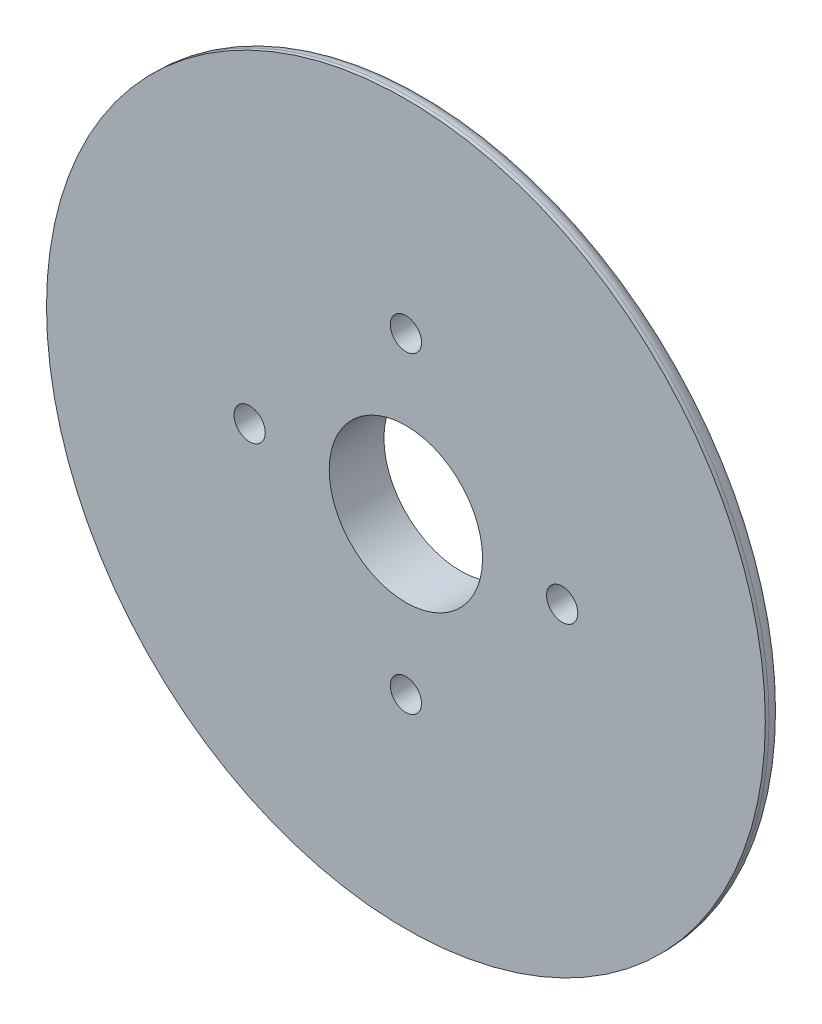
SolidWorks part; units mm, degrees
ref_plane "Front Plane" through (0, 0, 0) normal (0, 0, 1) x (1, 0, 0)
ref_plane "Top Plane" through (0, 0, 0) normal (0, 1, 0) x (1, 0, 0)
ref_plane "Right Plane" through (0, 0, 0) normal (1, 0, 0) x (0, 0, -1)
sketch "Sketch1" plane through (0, 0, 0) normal (0, 1, 0) x (1, 0, 0)
  line L0 (28, 45.5) -> (0, 45.5)
  line L1 (0, 45.5) -> (0, 16.5)
  line L2 (0, 16.5) -> (36, 16.5)
  line L3 (36, 16.5) -> (46, 26.5)
  line L4 (46, 26.5) -> (46, 40.5)
  line L5 (46, 40.5) -> (28, 45.5)
  line L6 (0, 45.5) -> (0, 16.5) construction
revolve "Revolve1" add sketch "Sketch1" angle 360 about L6
sketch "Sketch2" plane through (0, 0, -45.5) normal (0, 0, -1) x (-1, 0, 0)
  line L0 (-9.815, 0) -> (-4.9075, 8.5)
  line L1 (-4.9075, 8.5) -> (4.9075, 8.5)
  line L2 (4.9075, 8.5) -> (9.815, 0)
  line L3 (9.815, 0) -> (4.9075, -8.5)
  line L4 (4.9075, -8.5) -> (-4.9075, -8.5)
  line L5 (-4.9075, -8.5) -> (-9.815, 0)
extrude "Boss-Extrude1" add sketch "Sketch2" along normal blind 4
sketch "Sketch3" plane through (0, 0, -16.5) normal (0, 0, 1) x (1, 0, 0)
  circle A0 centre (0, 0) radius 1.5
extrude "Boss-Extrude2" add sketch "Sketch3" along normal blind 6
hole_wizard "Ø3.0 (3) Diameter Hole1" positions "Sketch5" profile "Sketch4" hole size "Ø3.0" standard "ANSI Metric"
sketch "Sketch5" plane through (0, 0, -16.5) normal (0, 0, 1) x (1, 0, 0)
  point P0 (-15.5, 0)
  point P1 (0, 15.5)
  point P2 (0, -15.5)
  point P3 (15.5, 0)
sketch "Sketch4" plane through (-15.5, 0, -16.5) normal (1, 0, 0) x (0, -1, 0)
  line L0 (0, 0) -> (0, 10)
  line L1 (0, 10) -> (1.5, 10)
  line L2 (1.5, 10) -> (1.5, 0)
  line L5 (1.5, 0) -> (0, 0)
  line L10 (0, 10) -> (-1.5, 10) construction
  line L11 (0, -6.35) -> (0, 107.95) construction
  dimension "Hole Dia." = 3
  dimension "Hole Depth" = 10
  dimension "Drill Angle" = 180
hole_wizard "Ø4.0 (4) Diameter Hole1" positions "Sketch7" profile "Sketch6" hole size "Ø4.0" standard "ANSI Metric"
sketch "Sketch7" plane through (0, 0, -45.5) normal (0, 0, -1) x (-1, 0, 0)
  point P0 (0, -20)
  point P1 (-20, 0)
  point P2 (20, 0)
  point P3 (0, 20)
sketch "Sketch6" plane through (0, -20, -45.5) normal (1, 0, 0) x (0, 1, 0)
  line L0 (0, 0) -> (0, 10)
  line L1 (0, 10) -> (2, 10)
  line L2 (2, 10) -> (2, 0)
  line L5 (2, 0) -> (0, 0)
  line L10 (0, 10) -> (-2, 10) construction
  line L11 (0, -6.35) -> (0, 107.95) construction
  dimension "Hole Dia." = 4
  dimension "Hole Depth" = 10
  dimension "Drill Angle" = 180
fillet "Fillet1" radius 2 2 edges at (46, 0, -40.5) (46, 0, -26.5)
fillet "Fillet2" radius 14.5 1 edges at (36, 0, -16.5)
sketch "Sketch8" plane through (0, 0, -16.5) normal (0, 0, 1) x (1, 0, 0)
  circle A0 centre (0, 0) radius 46
  circle A1 centre (0, 0) radius 46 construction
extrude "Cut-Extrude1" cut sketch "Sketch8" against normal blind 22 and the other way through all
sketch "Sketch9" plane through (0, 0, -49.5) normal (0, 0, -1) x (-1, 0, 0)
  circle A0 centre (0, 0) radius 9.815
extrude "Cut-Extrude2" cut sketch "Sketch9" against normal blind 21
